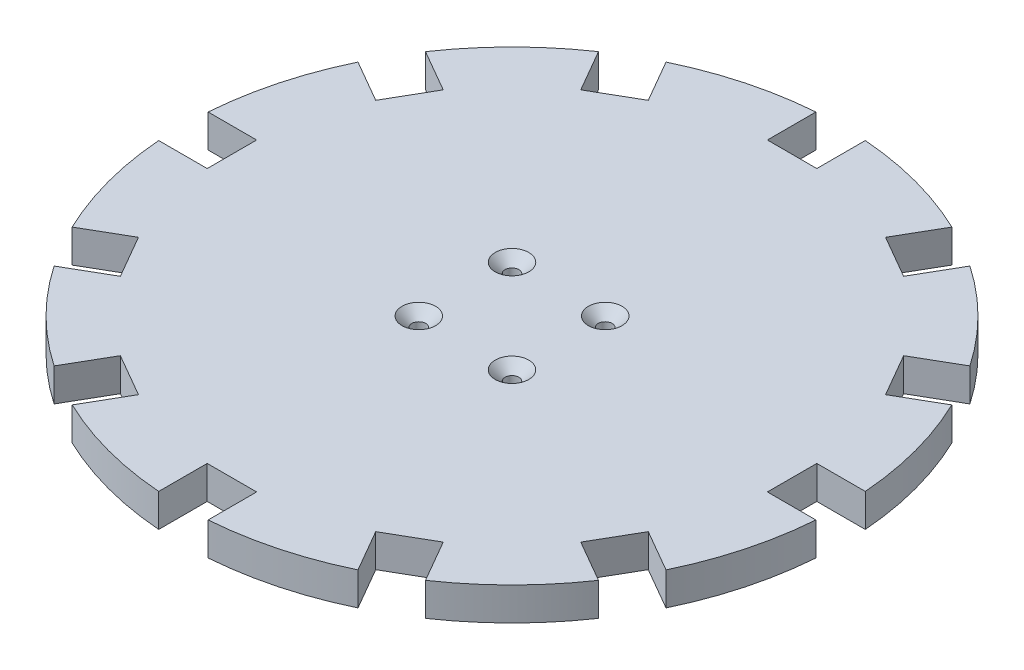
SolidWorks part; units mm, degrees
ref_plane "Ebene vorne" through (0, 0, 0) normal (0, 0, 1) x (1, 0, 0)
ref_plane "Ebene oben" through (0, 0, 0) normal (0, 1, 0) x (1, 0, 0)
ref_plane "Ebene rechts" through (0, 0, 0) normal (1, 0, 0) x (0, 0, -1)
sketch "Skizze1" plane through (0, 0, 0) normal (0, 1, 0) x (1, 0, 0)
  circle A0 centre (0, 0) radius 100
  dimension "D1" = 200
extrude "Aufsatz-Linear austragen1" add sketch "Skizze1" along normal blind 10
sketch "Skizze2" plane through (0, 10, 0) normal (0, 1, 0) x (1, 0, 0)
  line L0 (0, 0) -> (100, 0) construction
  line L1 (77.3622, -36.0048) -> (90.3525, -43.5048)
  line L2 (85, 7.5) -> (100, 7.5)
  line L3 (85, 7.5) -> (85, -7.5)
  line L4 (85, -7.5) -> (100, -7.5)
  line L5 (100, 7.5) -> (100, -7.5)
  line L6 (85, 7.5) -> (100, -7.5) construction
  line L7 (85, -7.5) -> (100, 7.5) construction
  line L8 (77.3622, -36.0048) -> (69.8622, -48.9952)
  line L9 (69.8622, -48.9952) -> (82.8525, -56.4952)
  line L10 (90.3525, -43.5048) -> (82.8525, -56.4952)
  line L11 (48.9952, -69.8622) -> (56.4952, -82.8525)
  line L12 (48.9952, -69.8622) -> (36.0048, -77.3622)
  line L13 (36.0048, -77.3622) -> (43.5048, -90.3525)
  line L14 (56.4952, -82.8525) -> (43.5048, -90.3525)
  line L15 (7.5, -85) -> (7.5, -100)
  line L16 (7.5, -85) -> (-7.5, -85)
  line L17 (-7.5, -85) -> (-7.5, -100)
  line L18 (7.5, -100) -> (-7.5, -100)
  line L19 (-36.0048, -77.3622) -> (-43.5048, -90.3525)
  line L20 (-36.0048, -77.3622) -> (-48.9952, -69.8622)
  line L21 (-48.9952, -69.8622) -> (-56.4952, -82.8525)
  line L22 (-43.5048, -90.3525) -> (-56.4952, -82.8525)
  line L23 (-69.8622, -48.9952) -> (-82.8525, -56.4952)
  line L24 (-69.8622, -48.9952) -> (-77.3622, -36.0048)
  line L25 (-77.3622, -36.0048) -> (-90.3525, -43.5048)
  line L26 (-82.8525, -56.4952) -> (-90.3525, -43.5048)
  line L27 (-85, -7.5) -> (-100, -7.5)
  line L28 (-85, -7.5) -> (-85, 7.5)
  line L29 (-85, 7.5) -> (-100, 7.5)
  line L30 (-100, -7.5) -> (-100, 7.5)
  line L31 (-77.3622, 36.0048) -> (-90.3525, 43.5048)
  line L32 (-77.3622, 36.0048) -> (-69.8622, 48.9952)
  line L33 (-69.8622, 48.9952) -> (-82.8525, 56.4952)
  line L34 (-90.3525, 43.5048) -> (-82.8525, 56.4952)
  line L35 (-48.9952, 69.8622) -> (-56.4952, 82.8525)
  line L36 (-48.9952, 69.8622) -> (-36.0048, 77.3622)
  line L37 (-36.0048, 77.3622) -> (-43.5048, 90.3525)
  line L38 (-56.4952, 82.8525) -> (-43.5048, 90.3525)
  line L39 (-7.5, 85) -> (-7.5, 100)
  line L40 (-7.5, 85) -> (7.5, 85)
  line L41 (7.5, 85) -> (7.5, 100)
  line L42 (-7.5, 100) -> (7.5, 100)
  line L43 (36.0048, 77.3622) -> (43.5048, 90.3525)
  line L44 (36.0048, 77.3622) -> (48.9952, 69.8622)
  line L45 (48.9952, 69.8622) -> (56.4952, 82.8525)
  line L46 (43.5048, 90.3525) -> (56.4952, 82.8525)
  line L47 (69.8622, 48.9952) -> (82.8525, 56.4952)
  line L48 (69.8622, 48.9952) -> (77.3622, 36.0048)
  line L49 (77.3622, 36.0048) -> (90.3525, 43.5048)
  line L50 (82.8525, 56.4952) -> (90.3525, 43.5048)
  circle A0 centre (0, 0) radius 100 construction
  point P10 (92.5, 0)
  point P12 (100, 0)
  point P58 (0, 0)
  dimension "D1" = 15
  dimension "D2" = 12
extrude "Schnitt-Linear austragen1" cut sketch "Skizze2" against normal through all
sketch "Skizze3" plane through (0, 0, 0) normal (0, -1, 0) x (1, 0, 0)
  circle A0 centre (0, 0) radius 52.5
  dimension "D1" = 105
extrude "Aufsatz-Linear austragen2" add sketch "Skizze3" along normal blind 10
chamfer "Fase1" distance 2 angle 45 1 edges at (0, -10, -52.5)
sketch "Skizze4" plane through (0, 10, 0) normal (0, 1, 0) x (1, 0, 0)
  line L0 (-14.1421, -14.1421) -> (14.1421, 14.1421) construction
  line L1 (14.1421, -14.1421) -> (-14.1421, 14.1421) construction
  line L2 (0, 0) -> (20, 0) construction
  circle A0 centre (0, 0) radius 20 construction
  circle A1 centre (-14.1421, 14.1421) radius 2.1
  circle A2 centre (14.1421, 14.1421) radius 2.1
  circle A3 centre (14.1421, -14.1421) radius 2.1
  circle A4 centre (-14.1421, -14.1421) radius 2.1
  dimension "D1" = 40
  dimension "D4" = 4.2
  dimension "D2" = 45
  dimension "D3" = 90
extrude "Schnitt-Linear austragen2" cut sketch "Skizze4" against normal through all
chamfer "Fase2" distance 3 angle 45 4 edges at (14.1421, 10, -12.0421) (14.1421, 10, 16.2421) (-14.1421, 10, 16.2421) (-14.1421, 10, -12.0421)
